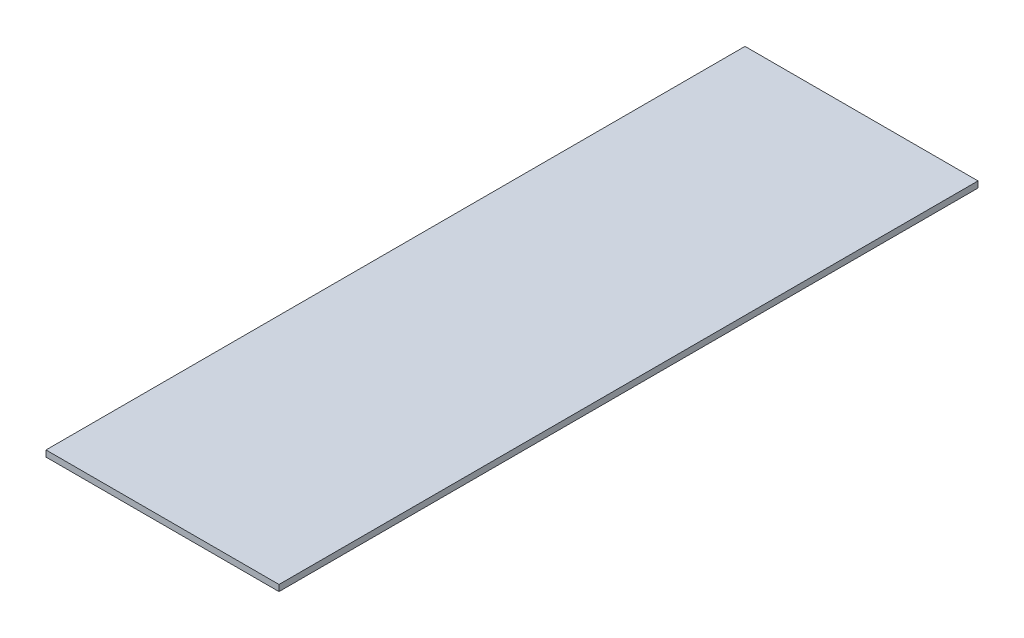
SolidWorks part; units mm, degrees
material "Acrylic (Medium-high impact)"
ref_plane "Front" through (0, 0, 0) normal (0, 0, 1) x (1, 0, 0)
ref_plane "Top" through (0, 0, 0) normal (0, 1, 0) x (1, 0, 0)
ref_plane "Right" through (0, 0, 0) normal (1, 0, 0) x (0, 0, -1)
sketch "Sketch1" plane through (0, 0, 0) normal (0, 1, 0) x (1, 0, 0)
  line L1 (-9.525, 28.575) -> (9.525, 28.575)
  line L2 (-9.525, 28.575) -> (-9.525, -28.575)
  line L3 (-9.525, -28.575) -> (9.525, -28.575)
  line L4 (9.525, 28.575) -> (9.525, -28.575)
  line L5 (-9.525, 28.575) -> (9.525, -28.575) construction
  line L6 (-9.525, -28.575) -> (9.525, 28.575) construction
  point P0 (0, 0)
  dimension "D1" = 19.05
  dimension "D2" = 57.15
extrude "Boss-Extrude1" add sketch "Sketch1" along normal blind 0.508
